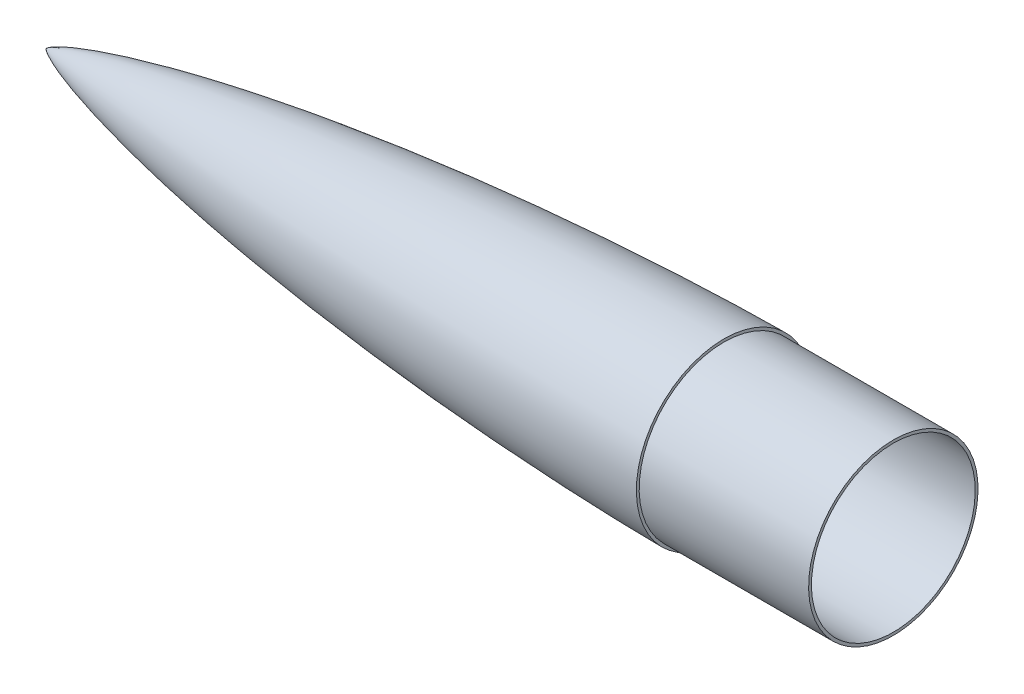
SolidWorks part; units mm, degrees
material "Hexcel AS4C (3000 Filaments)"
ref_plane "Plan de face"
ref_plane "Plan de dessus" through (0, 0, 0) normal (0, 1, 0) x (1, 0, 0)
ref_plane "Plan de droite" through (0, 0, 0) normal (1, 0, 0) x (0, 0, -1)
sketch "Esquisse1" plane through (0, 0, 0) normal (0, 0, 1) x (1, 0, 0)
  line L0 (2700, 0) -> (2700, 77.47) construction
  line L1 (2700, 77.47) -> (600, 77.47) construction
  line L2 (2700, 0) -> (0, 0) construction
  line L3 (600, 77.47) -> (600, 0)
  line L4 (1650, 77.47) -> (1650, 0) construction
  line L5 (600, 77.47) -> (600, 0) construction
  line L8 (0, 0) -> (600, 0)
  spline S0 degree 4 poles (0, 0) (0.0014, 0.0067) (0.0048, 0.0199) (0.0149, 0.0453) (0.0401, 0.0938) (0.0807, 0.157) (0.1383, 0.2334) (0.2203, 0.33) (0.3192, 0.4351) (0.4349, 0.5479) (0.5674, 0.6679) (0.7714, 0.8421) (1.1052, 1.1052) (1.6952, 1.526) (2.7478, 2.1929) (4.5887, 3.222) (7.8542, 4.817) (13.5227, 7.2186) (23.0835, 10.7182) (38.7362, 15.6536) (62.1009, 21.9639) (92.1582, 28.9163) (127.2376, 35.933) (164.7304, 42.4831) (202.346, 48.2813) (240.0557, 53.429) (277.8398, 57.9952) (315.6844, 62.0289) (353.5783, 65.5666) (391.513, 68.6356) (429.4812, 71.2564) (467.4769, 73.4429) (500.7425, 74.9827) (529.2668, 76.0339) (552.967, 76.7206) (569.499, 77.0956) (583.6166, 77.3332) (592.9784, 77.4344) (597.6594, 77.4658) (600, 77.47) knots 0 0 0 0 0 0.000045 0.00009 0.00018 0.000359 0.000539 0.000718 0.001013 0.001308 0.001601 0.001895 0.002778 0.004104 0.006368 0.010089 0.016647 0.028004 0.046856 0.077052 0.124599 0.187199 0.249799 0.312399 0.374999 0.4376 0.5002 0.5628 0.6254 0.688 0.7506 0.813201 0.875801 0.907101 0.938401 0.9692 0.9846 1 1 1 1 1 construction
  spline S1 degree 4 poles (0, 0) (0.0014, 0.0067) (0.0048, 0.0199) (0.0149, 0.0453) (0.0401, 0.0938) (0.0807, 0.157) (0.1383, 0.2334) (0.2203, 0.33) (0.3192, 0.4351) (0.4349, 0.5479) (0.5674, 0.6679) (0.7714, 0.8421) (1.1052, 1.1052) (1.6952, 1.526) (2.7478, 2.1929) (4.5887, 3.222) (7.8542, 4.817) (13.5227, 7.2186) (23.0835, 10.7182) (38.7362, 15.6536) (62.1009, 21.9639) (92.1582, 28.9163) (127.2376, 35.933) (164.7304, 42.4831) (202.346, 48.2813) (240.0557, 53.429) (277.8398, 57.9952) (315.6844, 62.0289) (353.5783, 65.5666) (391.513, 68.6356) (429.4812, 71.2564) (467.4769, 73.4429) (500.7425, 74.9827) (529.2668, 76.0339) (552.967, 76.7206) (569.499, 77.0956) (583.6166, 77.3332) (592.9784, 77.4344) (597.6594, 77.4658) (600, 77.47) knots 0 0 0 0 0 0.000045 0.00009 0.00018 0.000359 0.000539 0.000718 0.001013 0.001308 0.001601 0.001895 0.002778 0.004104 0.006368 0.010089 0.016647 0.028004 0.046856 0.077052 0.124599 0.187199 0.249799 0.312399 0.374999 0.4376 0.5002 0.5628 0.6254 0.688 0.7506 0.813201 0.875801 0.907101 0.938401 0.9692 0.9846 1 1 1 1 1
  point P4 (650, 111.3633)
  point P6 (0, 0)
  point P8 (0, 0)
  point P9 (0, 0)
  dimension "Ltot" = 2700
  dimension "R" = 77.47
  dimension "Ln" = 600
revolve "Révolution2" add sketch "Esquisse1" angle 360 about L2
sketch "Esquisse2" plane through (600, 0, 0) normal (1, 0, 0) x (0, 0, -1)
  circle A0 centre (0, 0) radius 75
  circle A1 centre (0, 0) radius 72.5
  dimension "D1" = 150
  dimension "D2" = 145
extrude "Boss.-Extru.1" add sketch "Esquisse2" along normal blind 150
